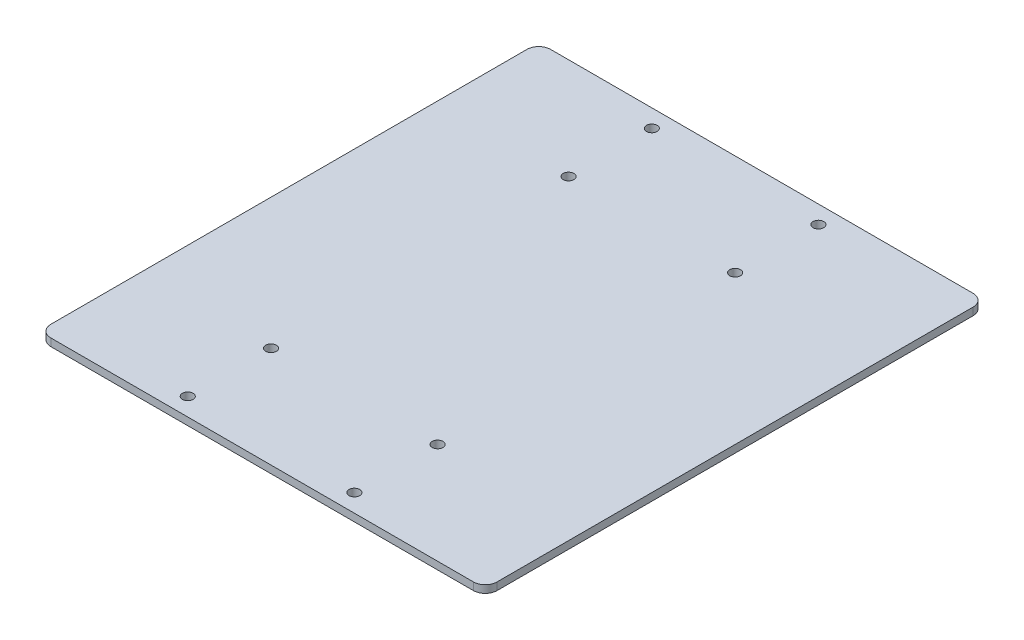
SolidWorks part; units mm, degrees
material "PE High Density"
ref_plane "Front Plane" through (0, 0, 0) normal (0, 0, 1) x (1, 0, 0)
ref_plane "Top Plane" through (0, 0, 0) normal (0, 1, 0) x (1, 0, 0)
ref_plane "Right Plane" through (0, 0, 0) normal (1, 0, 0) x (0, 0, -1)
sketch "Sketch1" plane through (0, 0, 0) normal (0, 1, 0) x (1, 0, 0)
  line L1 (-187.5, -210) -> (187.5, -210)
  line L2 (-187.5, -210) -> (-187.5, 210)
  line L3 (-187.5, 210) -> (187.5, 210)
  line L4 (187.5, -210) -> (187.5, 210)
  line L5 (-187.5, -210) -> (187.5, 210) construction
  line L6 (-187.5, 210) -> (187.5, -210) construction
  point P0 (0, 0)
  dimension "D1" = 375
  dimension "D2" = 420
extrude "Boss-Extrude1" add sketch "Sketch1" along normal blind 6.35
fillet "Fillet1" radius 10 4 edges at (-187.5, 3.175, -210) (187.5, 3.175, -210) (187.5, 3.175, 210) (-187.5, 3.175, 210)
hole_wizard "M8 Clearance Hole1" positions "Sketch2" profile "Sketch3" hole size "M8" standard "ANSI Metric" end condition through all
sketch "Sketch2" plane through (0, 6.35, 0) normal (0, 1, 0) x (1, 0, 0)
  line L1 (-77.5, -195) -> (62.5, -195)
  line L2 (-77.5, -195) -> (-77.5, -125)
  line L3 (-77.5, -125) -> (62.5, -125)
  line L4 (62.5, -195) -> (62.5, -125)
  line L5 (-177.5, -210) -> (177.5, -210) construction
  line L6 (-187.5, 200) -> (-187.5, -200) construction
  point P1 (-77.5, -195)
  point P2 (62.5, -125)
  point P45 (-77.5, -125)
  point P46 (62.5, -195)
  dimension "D1" = 140
  dimension "D2" = 70
  dimension "D3" = 15
  dimension "D4" = 110
sketch "Sketch3" plane through (-77.5, 6.35, 195) normal (1, 0, 0) x (0, 0, 1)
  line L0 (0, 0) -> (0, 6.35)
  line L1 (0, 6.35) -> (4.5, 6.35)
  line L2 (4.5, 6.35) -> (4.5, 0)
  line L5 (4.5, 0) -> (0, 0)
  line L11 (0, -6.35) -> (0, 107.95) construction
  dimension "Thru Hole Dia." = 9
  dimension "Thru Hole Depth" = 6.35
mirror "Mirror1" about plane through (0, 0, 0) normal (0, 0, 1) of "M8 Clearance Hole1"
